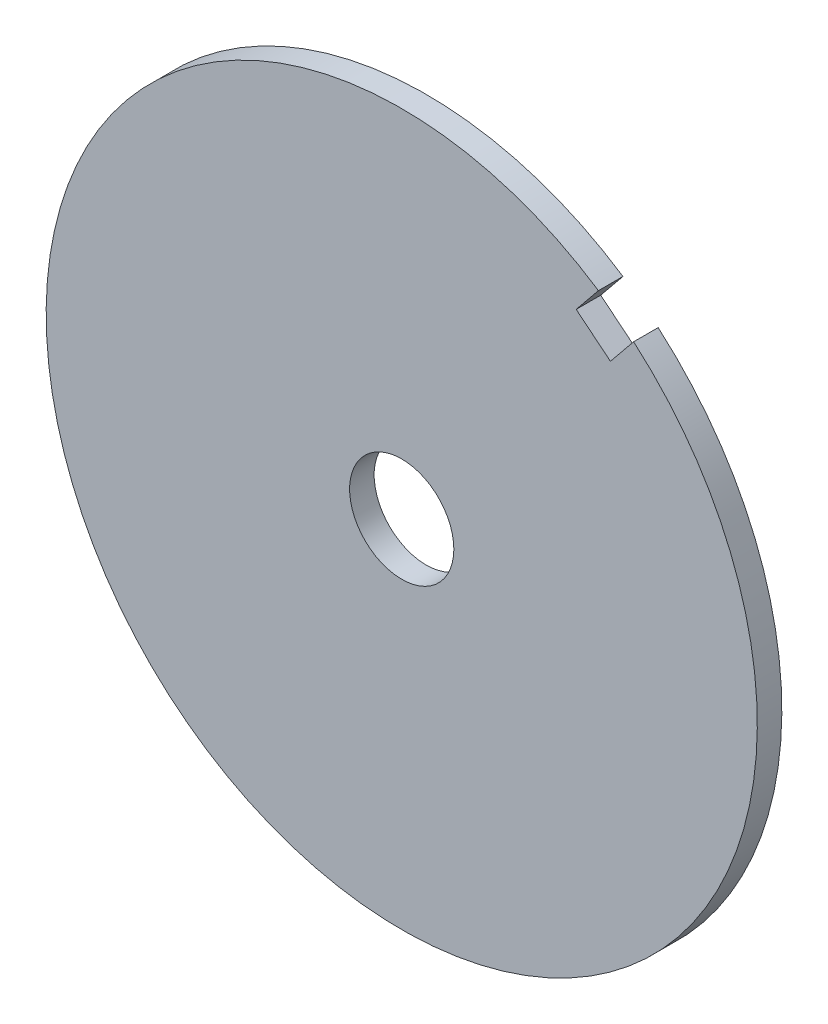
SolidWorks part; units mm, degrees
ref_plane "Front Plane" through (0, 0, 0) normal (0, 0, 1) x (1, 0, 0)
ref_plane "Top Plane" through (0, 0, 0) normal (0, 1, 0) x (1, 0, 0)
ref_plane "Right Plane" through (0, 0, 0) normal (1, 0, 0) x (0, 0, -1)
sketch "Sketch1" plane through (0, 0, 3372.7778) normal (0, 0, 1) x (1, 0, 0)
  circle A0 centre (0, 0) radius 92.075
  dimension "D1" = 184.15
extrude "Boss-Extrude1" add sketch "Sketch1" along normal blind 6.35
sketch "Sketch2" plane through (0, 0, 3379.1278) normal (0, 0, 1) x (1, 0, 0)
  circle A0 centre (0, 0) radius 13.4938
  dimension "D1" = 26.9875
extrude "Cut-Extrude1" cut sketch "Sketch2" against normal up to next
sketch "Sketch3" plane through (0, 0, 3379.1278) normal (0, 0, 1) x (1, 0, 0)
  line L0 (50.9358, 76.703) -> (45.1744, 69.6206)
  line L1 (45.1744, 69.6206) -> (54.0412, 62.4077)
  line L2 (54.0412, 62.4077) -> (60.0519, 69.7967)
  line L3 (149.8565, 194.2811) -> (76.2187, 103.7583) construction
  line L4 (81.1447, 99.7511) -> (154.7825, 190.274) construction
  circle A0 centre (0, 0) radius 92.075 construction
  dimension "D1" = 2.54
  dimension "D2" = 2.54
  dimension "D3" = 9.525
extrude "Cut-Extrude2" cut sketch "Sketch3" against normal through all and the other way through all
